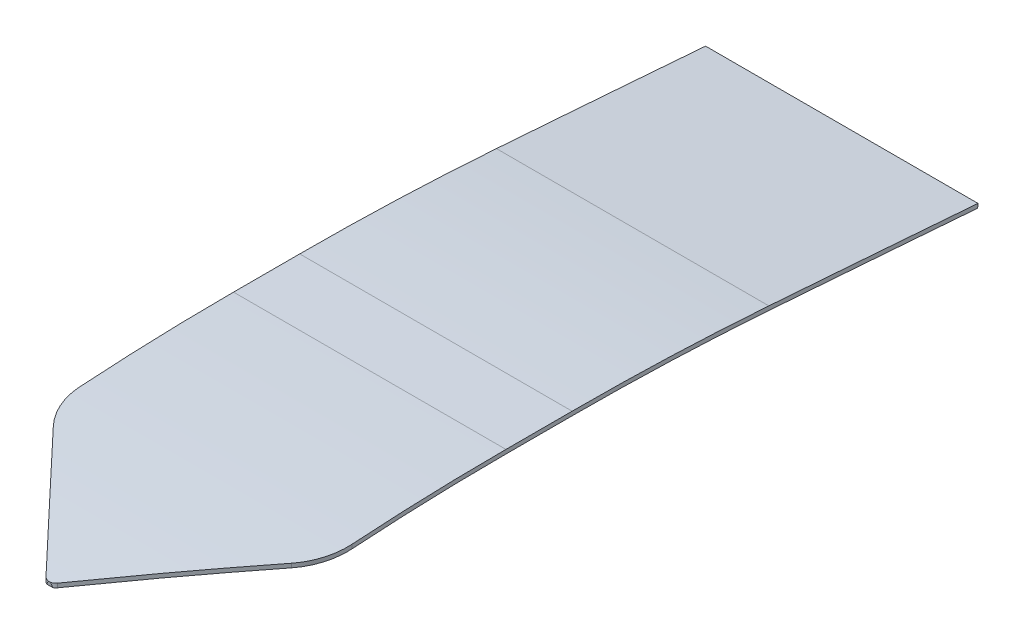
SolidWorks part; units mm, degrees
ref_plane "Front Plane" through (0, 0, 0) normal (0, 0, 1) x (1, 0, 0)
ref_plane "Top Plane" through (0, 0, 0) normal (0, 1, 0) x (1, 0, 0)
ref_plane "Right Plane" through (0, 0, 0) normal (1, 0, 0) x (0, 0, -1)
sketch "Sketch1" plane through (221.2232, 2174.8893, 3089.3536) normal (1, 0, 0) x (0, 0, -1)
  line L1 (20.32, -469.9) -> (0, -469.9) construction
  line L4 (20.32, -469.9) -> (0, -469.9) construction
  line L36 (418.4703, 343.8483) -> (835.7994, 343.8483) construction
  line L37 (418.4703, 343.8483) -> (835.7994, 343.8483)
  line L40 (418.4703, 318.4483) -> (835.7994, 318.4483)
  line L41 (-1602.5297, 202.624) -> (-1598.9972, 177.4709)
  line L42 (3395.4703, 198.9533) -> (3393.4944, 173.6302)
  arc A0 (2076.5794, 298.5837) -> (1699.8995, 321.9101) centre (835.7994, -16684.7351) ccw construction
  arc A2 (1699.8995, 321.9101) -> (1433.1995, 333.366) centre (835.7994, -16684.7351) ccw construction
  arc A6 (1433.1995, 333.366) -> (835.7994, 343.8483) centre (835.7994, -16684.7351) ccw construction
  arc A7 (2076.5794, 298.5837) -> (1699.8995, 321.9101) centre (835.7994, -16684.7351) ccw
  arc A8 (1699.8995, 321.9101) -> (1433.1995, 333.366) centre (835.7994, -16684.7351) ccw
  arc A9 (1433.1995, 333.366) -> (835.7994, 343.8483) centre (835.7994, -16684.7351) ccw
  arc A10 (418.4703, 343.8483) -> (-1602.5297, 202.624) centre (418.4703, -14187.6006) ccw
  arc A11 (2076.5794, 298.5837) -> (3395.4703, 198.9533) centre (-17442.8336, -266875.6126) cw
  arc A12 (2074.7287, 273.2512) -> (3393.4944, 173.6302) centre (-17442.8336, -266875.6126) cw
  arc A13 (2074.7287, 273.2512) -> (1698.6106, 296.5429) centre (835.7994, -16684.7351) ccw
  arc A14 (1698.6106, 296.5429) -> (1432.3084, 307.9816) centre (835.7994, -16684.7351) ccw
  arc A15 (1432.3084, 307.9816) -> (835.7994, 318.4483) centre (835.7994, -16684.7351) ccw
  arc A16 (418.4703, 318.4483) -> (-1598.9972, 177.4709) centre (418.4703, -14187.6006) ccw
  dimension "D2" = 4998
  dimension "D1" = 2021
  dimension "D4" = 14531.4488
  dimension "D5" = 267886.2793
  dimension "D6" = 17028.5833
  dimension "D7" = 17028.5833
  dimension "D8" = 417.3291
  dimension "D3" = 1318.8908
  dimension "D10" = 1658.1092
  dimension "D9" = 25.4
extrude "Boss-Extrude1" add sketch "Sketch1" along normal blind 1562 and the other way blind 176
sketch "Sketch2" plane through (0, 0, 0) normal (0, 1, 0) x (1, 0, 0)
  line L0 (950.67, -4676.1125) -> (1664.7977, -3915.7161)
  line L1 (914.2232, 306.1166) -> (914.2232, -7016.6759) construction
  line L2 (45.2232, 306.1166) -> (1783.2232, 306.1166) construction
  line L5 (1773.2232, -3800.2656) -> (55.2232, -3800.2656) construction
  line L8 (1773.2232, -3641.8834) -> (1773.2232, 306.1166)
  line L9 (1773.2232, 306.1166) -> (55.2232, 306.1166)
  line L10 (55.2232, 306.1166) -> (55.2232, -3641.8834)
  line L12 (2470.299, 1079.7144) -> (-893.2768, 1079.7144)
  line L13 (2470.299, 1079.7144) -> (2470.299, -4890.7405)
  line L14 (2470.299, -4890.7405) -> (-893.2768, -4890.7405)
  line L15 (-893.2768, 1079.7144) -> (-893.2768, -4890.7405)
  line L16 (45.2232, 306.1166) -> (1783.2232, 306.1166) construction
  line L17 (163.6487, -3915.7161) -> (877.7764, -4676.1125)
  line L18 (55.2232, -3641.8834) -> (1773.2232, -3641.8834) construction
  line L19 (45.2232, -4691.8834) -> (1783.2232, -4691.8834) construction
  arc A3 (950.67, -4676.1125) -> (877.7764, -4676.1125) centre (914.2232, -4641.8834) cw
  arc A4 (1664.7977, -3915.7161) -> (1773.2232, -3641.8834) centre (1373.2232, -3641.8834) ccw
  arc A5 (55.2232, -3641.8834) -> (163.6487, -3915.7161) centre (455.2232, -3641.8834) ccw
  point P21 (914.2232, 306.1166)
  dimension "D1" = 50
  dimension "D3" = 400
  dimension "D2" = 1718
  dimension "D4" = 1000
  dimension "D5" = 1050
  dimension "D6" = 4998
extrude "Cut-Extrude2" cut sketch "Sketch2" along normal blind 6472
ref_plane "Plane1" through (914.2232, 0, 0) normal (1, 0, 0) x (0, 0, -1)
